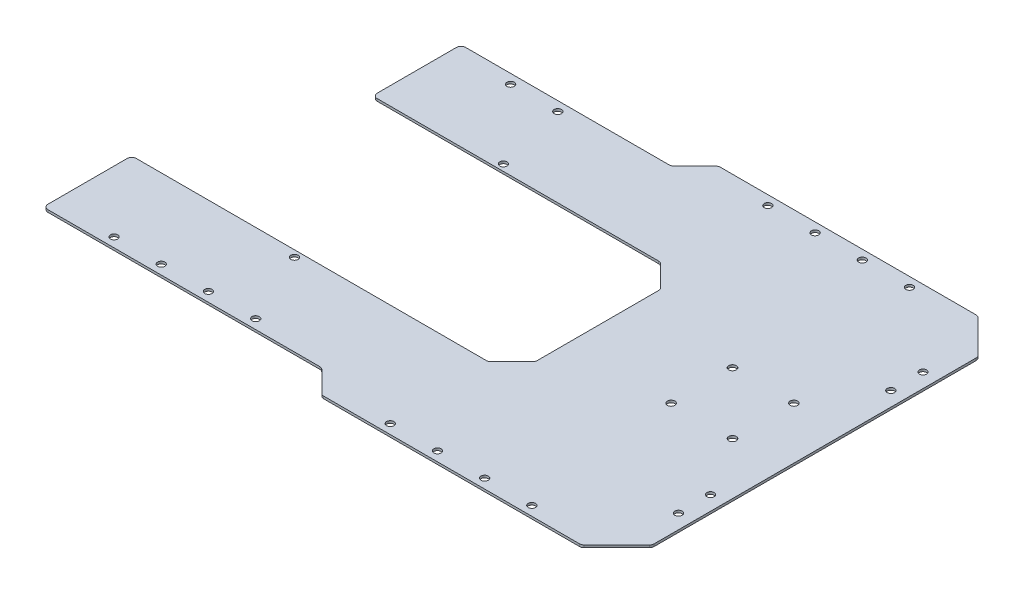
SolidWorks part; units mm, degrees
material "Thornel Mat VMA"
ref_plane "前视基准面" through (0, 0, 0) normal (0, 0, 1) x (1, 0, 0)
ref_plane "上视基准面" through (0, 0, 0) normal (0, 1, 0) x (1, 0, 0)
ref_plane "右视基准面" through (0, 0, 0) normal (1, 0, 0) x (0, 0, -1)
other "Configuration Table"
sketch "草图1" plane through (0, 0, 0) normal (0, 1, 0) x (1, 0, 0)
  line L1 (-13, 13) -> (13, 13) construction
  line L2 (-13, 13) -> (-13, -13) construction
  line L3 (-13, -13) -> (13, -13) construction
  line L4 (13, 13) -> (13, -13) construction
  line L5 (-13, 13) -> (13, -13) construction
  line L6 (-13, -13) -> (13, 13) construction
  line L7 (-35, 35) -> (35, 35)
  line L8 (-35, 35) -> (-35, -35)
  line L9 (-35, -35) -> (35, -35)
  line L10 (35, 35) -> (35, -35)
  line L11 (-35, 35) -> (35, -35) construction
  line L12 (-35, -35) -> (35, 35) construction
  circle A0 centre (13, -13) radius 1.6
  circle A1 centre (13, 13) radius 1.6
  circle A2 centre (-13, 13) radius 1.6
  circle A3 centre (-13, -13) radius 1.6
  point P0 (0, 0)
  point P10 (0, 0)
  dimension "D2" = 3.2
  dimension "D1" = 26
  dimension "D3" = 22
extrude "凸台-拉伸1" add sketch "草图1" along normal blind 1
sketch "草图2" plane through (0, 0, 0) normal (0, -1, 0) x (1, 0, 0)
  line L0 (35, -35) -> (35, -69)
  line L1 (35, -69) -> (20, -84)
  line L2 (20, -84) -> (-90, -84)
  line L3 (-90, -84) -> (-100, -74)
  line L4 (-100, -74) -> (-189, -74)
  line L5 (0, 0) -> (-22.8005, 0) construction
  line L6 (-100, 74) -> (-218, 74)
  line L7 (-90, 84) -> (-100, 74)
  line L8 (20, 84) -> (-90, 84)
  line L9 (35, 69) -> (20, 84)
  line L10 (35, 35) -> (35, 69)
  line L11 (-189, -74) -> (-189, -36.5)
  line L12 (-189, -36.5) -> (-57, -36.5)
  line L15 (-57, -36.5) -> (-57, 36.5)
  line L16 (-57, 36.5) -> (-218, 36.5)
  line L17 (-218, 36.5) -> (-218, 74)
  line L19 (35, 35) -> (-35, 35)
  line L20 (-35, 35) -> (-35, -35)
  line L21 (-35, -35) -> (35, -35)
  circle A0 centre (0, -50) radius 34 construction
  circle A3 centre (0, 50) radius 34 construction
  dimension "D3" = 68
  dimension "D1" = 135
  dimension "D2" = 50
  dimension "D4" = 135
  dimension "D5" = 10
  dimension "D6" = 110
  dimension "D7" = 224
  dimension "D8" = 73
  dimension "D9" = 36.5
  dimension "D10" = 253
  dimension "D11" = 92
  dimension "D12" = 15
extrude "凸台-拉伸2" add sketch "草图2" against normal blind 1
ref_plane "基准面1" through (0, 70, 0) normal (0, 1, 0) x (1, 0, 0)
sketch "草图3" plane through (0, 70, 0) normal (0, 1, 0) x (1, 0, 0)
  line L14 (35, -69) -> (35, 69)
  line L15 (35, 69) -> (20, 84)
  line L16 (20, 84) -> (-90, 84)
  line L17 (-90, 84) -> (-100, 74)
  line L18 (-100, 74) -> (-189, 74)
  line L19 (-189, 74) -> (-189, 36.5)
  line L20 (-189, 36.5) -> (-57, 36.5)
  line L21 (-57, 36.5) -> (-57, -36.5)
  line L22 (-57, -36.5) -> (-218, -36.5)
  line L23 (-218, -36.5) -> (-218, -74)
  line L24 (-218, -74) -> (-100, -74)
  line L25 (-100, -74) -> (-90, -84)
  line L26 (-90, -84) -> (20, -84)
  line L27 (20, -84) -> (35, -69)
  line L28 (35, -69) -> (35, 69)
  line L29 (35, 69) -> (20, 84)
  line L30 (20, 84) -> (-90, 84)
  line L31 (-90, 84) -> (-100, 74)
  line L32 (-100, 74) -> (-189, 74)
  line L33 (-189, 74) -> (-189, 36.5)
  line L34 (-189, 36.5) -> (-57, 36.5)
  line L35 (-57, 36.5) -> (-57, -36.5)
  line L36 (-57, -36.5) -> (-218, -36.5)
  line L37 (-218, -36.5) -> (-218, -74)
  line L38 (-218, -74) -> (-100, -74)
  line L39 (-100, -74) -> (-90, -84)
  line L40 (-90, -84) -> (20, -84)
  line L41 (20, -84) -> (35, -69)
  dimension "D1" = 0
extrude "凸台-拉伸3" [suppressed] add sketch "草图3" along normal blind 1 separate body
sketch "草图4" [suppressed] plane through (0, 70, 0) normal (0, -1, 0) x (1, 0, 0)
  line L0 (-58, 37.5) -> (-231, 37.5)
  line L1 (-231, 37.5) -> (-231, 71)
  line L2 (-231, 71) -> (-100.9745, 71)
  line L3 (-100.9745, 71) -> (-90.9745, 81)
  line L4 (-90.9745, 81) -> (10.5514, 81)
  line L5 (10.5514, 81) -> (32, 59.5514)
  line L6 (32, 59.5514) -> (32, -56.5959)
  line L7 (32, -56.5959) -> (7.5959, -81)
  line L8 (7.5959, -81) -> (-96.331, -81)
  line L9 (-96.331, -81) -> (-106.331, -71)
  line L10 (-106.331, -71) -> (-188, -71)
  line L11 (-188, -71) -> (-188, -37.5)
  line L12 (-188, -37.5) -> (-58, -37.5)
  line L13 (-58, -37.5) -> (-58, 37.5)
  line L14 (33, 62.2548) -> (13.2548, 82)
  line L15 (13.2548, 82) -> (-96.7452, 82)
  line L16 (-96.7452, 82) -> (-106.7452, 72)
  line L17 (-106.7452, 72) -> (-232, 72)
  line L18 (-232, 72) -> (-232, 36.5)
  line L19 (-232, 36.5) -> (-59, 36.5)
  line L20 (-59, 36.5) -> (-59, -36.5)
  line L21 (-59, -36.5) -> (-189, -36.5)
  line L22 (-189, -36.5) -> (-189, -72)
  line L23 (-189, -72) -> (-106.7452, -72)
  line L24 (-106.7452, -72) -> (-96.7452, -82)
  line L25 (-96.7452, -82) -> (13.2548, -82)
  line L26 (13.2548, -82) -> (33, -62.2548)
  line L27 (33, -62.2548) -> (33, 62.2548)
  line L28 (33, 62.2548) -> (13.2548, 82)
  line L29 (13.2548, 82) -> (-96.7452, 82)
  line L30 (-96.7452, 82) -> (-106.7452, 72)
  line L31 (-106.7452, 72) -> (-232, 72)
  line L32 (-232, 72) -> (-232, 36.5)
  line L33 (-232, 36.5) -> (-59, 36.5)
  line L34 (-59, 36.5) -> (-59, -36.5)
  line L35 (-59, -36.5) -> (-189, -36.5)
  line L36 (-189, -36.5) -> (-189, -72)
  line L37 (-189, -72) -> (-106.7452, -72)
  line L38 (-106.7452, -72) -> (-96.7452, -82)
  line L39 (-96.7452, -82) -> (13.2548, -82)
  line L40 (13.2548, -82) -> (33, -62.2548)
  line L41 (33, -62.2548) -> (33, 62.2548)
  dimension "D2" = 1
  dimension "D3" = 1
  dimension "D4" = 1
  dimension "D5" = 1
  dimension "D6" = 1
  dimension "D7" = 1
  dimension "D8" = 1
  dimension "D9" = 1
  dimension "D10" = 1
  dimension "D11" = 1
  dimension "D12" = 1
  dimension "D1" = 0
extrude "凸台-拉伸4" [suppressed] add sketch "草图4" along normal blind 50
sketch "草图5" plane through (0, 1, 0) normal (0, 1, 0) x (1, 0, 0)
  circle A0 centre (-146.3, -39.25) radius 1.55
  circle A1 centre (-136.3, 39.25) radius 1.55
  dimension "D1" = 3.1
extrude "切除-拉伸1" cut sketch "草图5" against normal blind 10
sketch "草图6" plane through (0, 0, 0) normal (0, -1, 0) x (1, 0, 0)
  circle A0 centre (28.9, 51.8) radius 1.55
  circle A1 centre (28.9, 38.2) radius 1.55
  circle A2 centre (28.9, -51.8) radius 1.55
  circle A3 centre (28.9, -38.2) radius 1.55
  circle A4 centre (-5, 80) radius 1.55
  circle A5 centre (-25, 80) radius 1.55
  circle A6 centre (-132, 70) radius 1.55
  circle A7 centre (-152, 70) radius 1.55
  circle A8 centre (-144, -70) radius 1.55
  circle A9 centre (-164, -70) radius 1.55
  circle A10 centre (-5, -80) radius 1.55
  circle A11 centre (-25, -80) radius 1.55
  circle A12 centre (-45, 80) radius 1.55
  circle A13 centre (-65, 80) radius 1.55
  circle A14 centre (-45, -80) radius 1.55
  circle A15 centre (-65, -80) radius 1.55
  circle A16 centre (-192, 70) radius 1.55
  circle A17 centre (-172, 70) radius 1.55
  dimension "D1" = 3.1
extrude "切除-拉伸2" cut sketch "草图6" against normal blind 10
chamfer "倒角1" distance 10 angle 45 2 edges at (-57, 0.5, -36.5) (-57, 0.5, 36.5)
fillet "圆角1" radius 2 16 edges at (35, 0.5, 69) (20, 0.5, 84) (-90, 0.5, 84) (-100, 0.5, 74) (-218, 0.5, 74) (-218, 0.5, 36.5) (-67, 0.5, 36.5) (-57, 0.5, 26.5) (-57, 0.5, -26.5) (-67, 0.5, -36.5) (-189, 0.5, -36.5) (-189, 0.5, -74) (-100, 0.5, -74) (20, 0.5, -84) (35, 0.5, -69) (-90, 0.5, -84)
